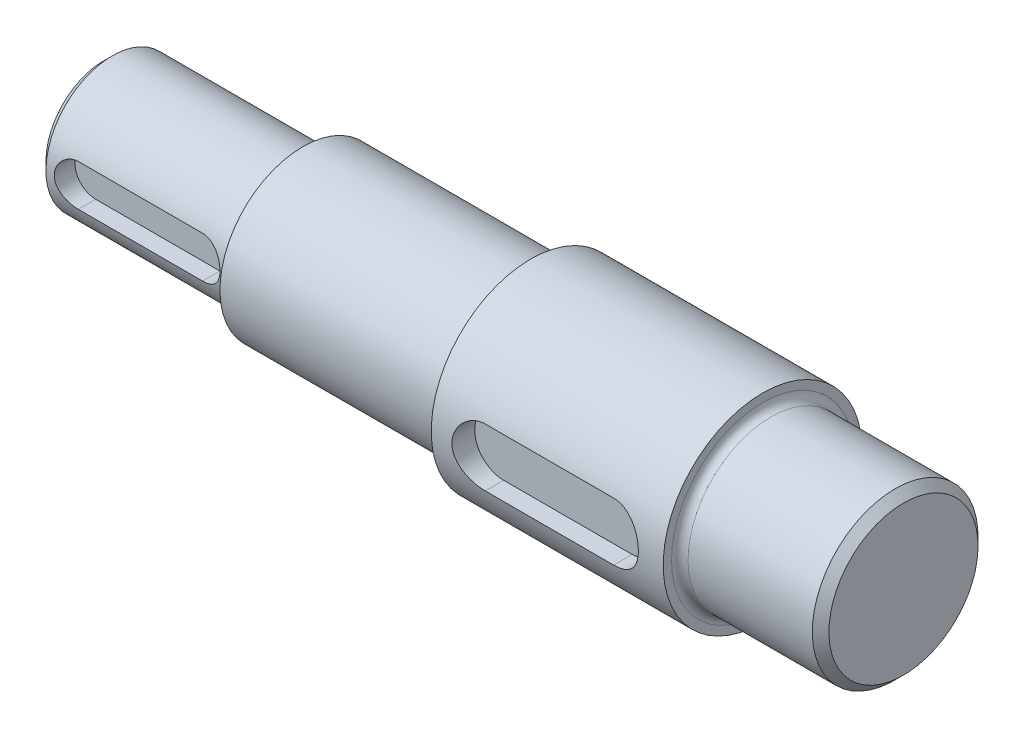
SolidWorks part; units mm, degrees
ref_plane "Спереди" through (0, 0, 0) normal (0, 0, 1) x (1, 0, 0)
ref_plane "Сверху" through (0, 0, 0) normal (0, 1, 0) x (1, 0, 0)
ref_plane "Справа" through (0, 0, 0) normal (1, 0, 0) x (0, 0, -1)
sketch "Эскиз1" plane through (0, 0, 0) normal (0, 0, 1) x (1, 0, 0)
  line L0 (0, 0) -> (0, 16)
  line L1 (0, 16) -> (48, 16)
  line L2 (48, 16) -> (48, 20)
  line L3 (48, 20) -> (103, 20)
  line L4 (103, 20) -> (103, 24)
  line L5 (103, 24) -> (159, 24)
  line L6 (159, 24) -> (159, 20)
  line L7 (159, 20) -> (193, 20)
  line L8 (193, 20) -> (193, 0)
  line L9 (193, 0) -> (0, 0) construction
  line L10 (0, 0) -> (193, 0)
  dimension "D1" = 32
  dimension "D2" = 40
  dimension "D3" = 48
  dimension "D4" = 48
  dimension "D5" = 103
  dimension "D6" = 34
  dimension "D7" = 193
revolve "Повернуть1" add sketch "Эскиз1" angle 360 about L9
chamfer "Фаска1" distance 2 angle 45 2 edges at (0, 16, 0) (193, 20, 0)
fillet "Скругление1" radius 2 3 edges at (48, 16, 0) (103, 20, 0) (159, 20, 0)
ref_plane "Плоскость1" through (0, 0, 16) normal (0, 0, 1) x (1, 0, 0)
sketch "Эскиз2" plane through (0, 0, 16) normal (0, 0, 1) x (1, 0, 0)
  line L0 (-9.6258, 0) -> (201.7216, 0) construction
  line L1 (9, 0) -> (39, 0) construction
  line L2 (9, 5) -> (39, 5)
  line L3 (9, -5) -> (39, -5)
  line L4 (0, 14) -> (0, -14) construction
  arc A0 (9, 5) -> (9, -5) centre (9, 0) ccw
  arc A1 (39, -5) -> (39, 5) centre (39, 0) ccw
  point P5 (24, 0)
  dimension "D3" = 5
  dimension "D1" = 9
  dimension "D2" = 30
extrude "Вырез-Вытянуть1" cut sketch "Эскиз2" against normal blind 5
ref_plane "Плоскость2" through (0, 0, 24) normal (0, 0, 1) x (1, 0, 0)
sketch "Эскиз3" plane through (0, 0, 24) normal (0, 0, 1) x (1, 0, 0)
  line L0 (0, 0) -> (203.982, 0) construction
  line L1 (115, 0) -> (146, 0) construction
  line L2 (115, 7) -> (146, 7)
  line L3 (115, -7) -> (146, -7)
  line L4 (103, 24) -> (103, -24) construction
  arc A0 (115, 7) -> (115, -7) centre (115, 0) ccw
  arc A1 (146, -7) -> (146, 7) centre (146, 0) ccw
  point P5 (130.5, 0)
  dimension "D3" = 7
  dimension "D1" = 12
  dimension "D2" = 31
extrude "Вырез-Вытянуть2" cut sketch "Эскиз3" against normal blind 5.5
